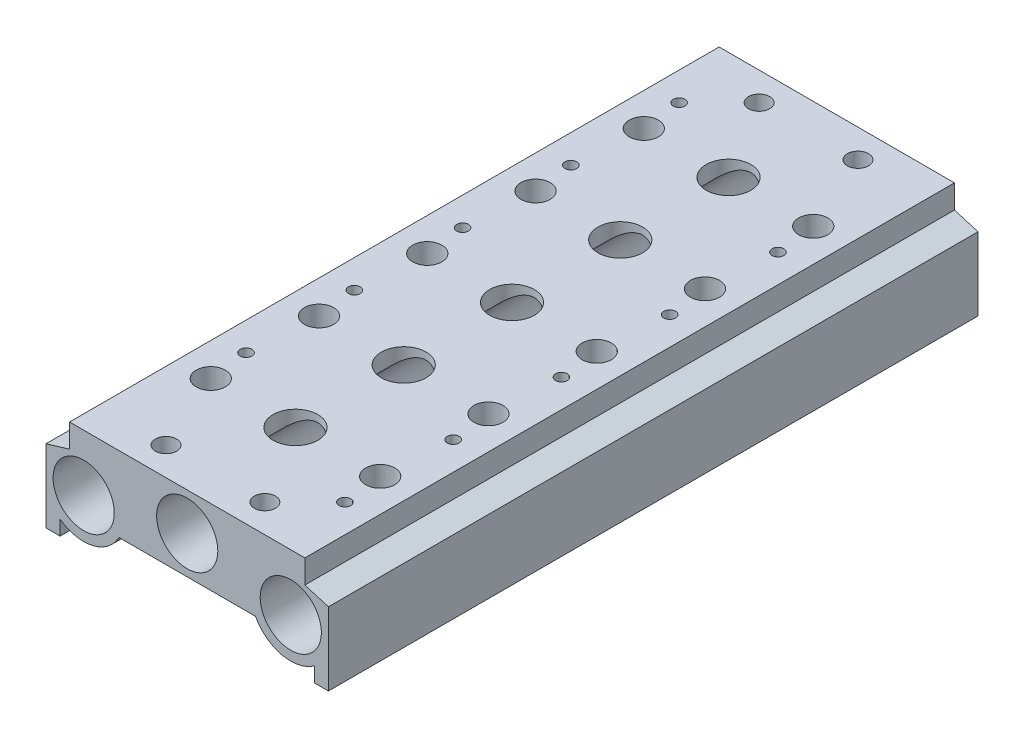
SolidWorks part; units mm, degrees
ref_plane "前视基准面" through (0, 0, 0) normal (0, 0, 1) x (1, 0, 0)
ref_plane "上视基准面" through (0, 0, 0) normal (0, 1, 0) x (1, 0, 0)
ref_plane "右视基准面" through (0, 0, 0) normal (1, 0, 0) x (0, 0, -1)
sketch "草图1" plane through (0, 0, 0) normal (0, 0, 1) x (1, 0, 0)
  line L0 (-14.5, -5) -> (14.5, -5)
  line L1 (-25, 11) -> (25, 11)
  line L2 (-30, 4.5) -> (-30, -11)
  line L3 (-30, -11) -> (-27, -11)
  line L4 (30, 4.5) -> (30, -11)
  line L5 (-27, -7.8739) -> (-27, -11)
  line L6 (0, 3) -> (0, -11) construction
  line L7 (-25, 11) -> (-25, 6)
  line L8 (25, 11) -> (25, 6)
  line L10 (-25, -5) -> (25, -5) construction
  line L11 (27, -7.8739) -> (27, -11)
  line L12 (30, 4.5) -> (25, 6)
  line L13 (-30, 4.5) -> (-25, 6)
  line L15 (27, -11) -> (30, -11)
  circle A0 centre (0, 3) radius 6.5
  circle A1 centre (-22, -1) radius 6.5
  arc A2 (27, -7.8739) -> (14.5, -5) centre (22, -1) cw
  circle A3 centre (22, -1) radius 6.5
  arc A4 (-27, -7.8739) -> (-14.5, -5) centre (-22, -1) ccw
  dimension "D4" = 13
  dimension "D1" = 16
extrude "凸台-拉伸1" add sketch "草图1" along normal mid plane 138
sketch "草图2" plane through (0, 11, 0) normal (0, 1, 0) x (1, 0, 0)
  circle A0 centre (10.5, 63) radius 2.25
  circle A1 centre (-10.5, 63) radius 2.25
  dimension "D4" = 4.5
extrude "切除-拉伸1" cut sketch "草图2" against normal up to next
mirror "镜向1" about plane through (0, 0, 0) normal (0, 0, 1) of "切除-拉伸1"
sketch "草图3" plane through (0, 11, 0) normal (0, 1, 0) x (1, 0, 0)
  circle A0 centre (0, 46) radius 4.75
  circle A1 centre (-18, 46) radius 3.1
  circle A2 centre (18, 46) radius 3.1
  dimension "D3" = 9.5
  dimension "D4" = 6.2
  dimension "D5" = 18
  dimension "D6" = 18
extrude "切除-拉伸2" cut sketch "草图3" against normal blind 12
hole_wizard "M3 螺纹孔1" positions "草图5" profile "草图4" tap size "M3" standard "ISO"
sketch "草图5" plane through (0, 11, 0) normal (0, 1, 0) x (-1, 0, 0)
  line L0 (-25, -69) -> (25, -69) construction
  line L2 (30, 69) -> (30, -69) construction
  line L3 (-30, 69) -> (-30, -69) construction
  point P0 (19, -54.5)
  point P1 (-19, -37.5)
  dimension "D2" = 11
  dimension "D1" = 14.5
  dimension "D3" = 11
  dimension "D4" = 31.5
sketch "草图4" plane through (-19, 11, -54.5) normal (1, 0, 0) x (0, 0, 1)
  line L0 (0, 0) -> (0, 8.2511)
  line L1 (0, 8.2511) -> (1.25, 7.5)
  line L2 (1.25, 7.5) -> (1.25, 0)
  line L5 (1.25, 0) -> (0, 0)
  line L10 (0, 8.2511) -> (-1.25, 7.5) construction
  line L11 (0, -6.35) -> (0, 107.95) construction
  dimension "螺纹孔钻头直径" = 2.5
  dimension "螺纹孔钻头深度" = 7.5
  dimension "导头角度" = 118
cosmetic thread "孔螺蚊线1" parameters "D1"=6, "D2"=3
cosmetic thread "孔螺蚊线2" parameters "D1"=6, "D2"=3
pattern_linear "阵列(线性)1" count 5 spacing 23 along (0, 0, 1) of "切除-拉伸2"
pattern_linear "阵列(线性)2" count 5 spacing 23 along (0, 0, 1) of "M3 螺纹孔1"
